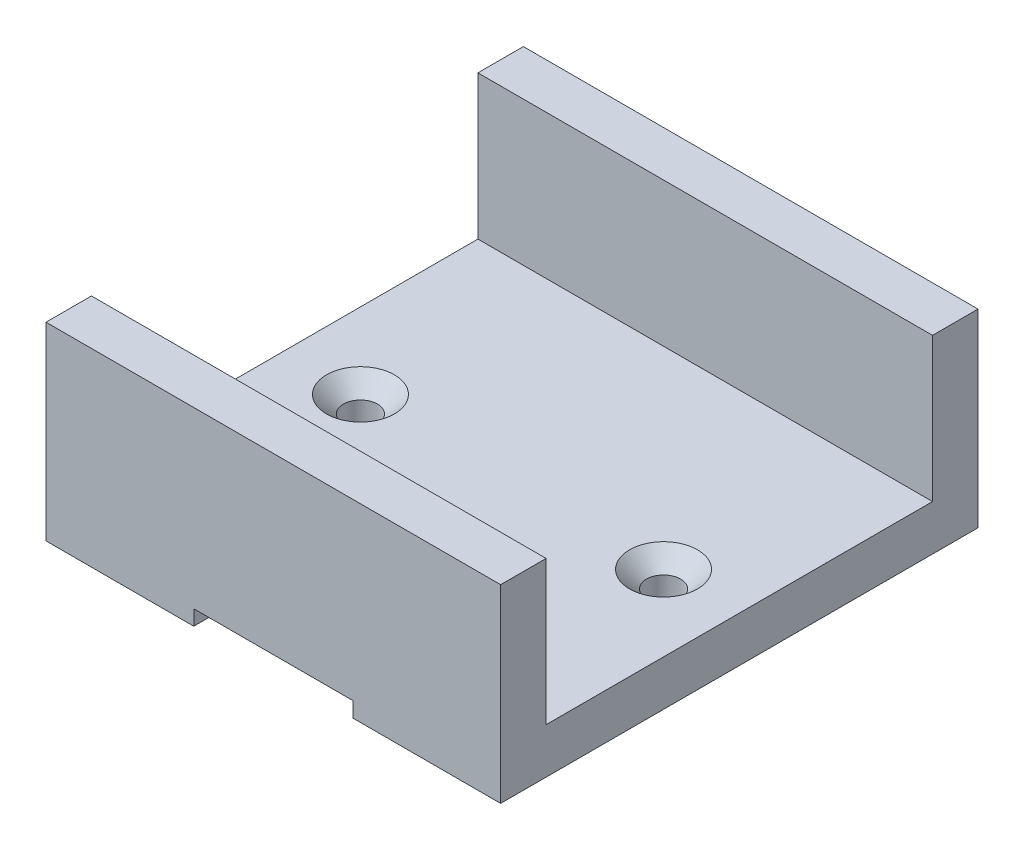
SolidWorks part; units mm, degrees
ref_plane "Front Plane" through (0, 0, 0) normal (0, 0, 1) x (1, 0, 0)
ref_plane "Top Plane" through (0, 0, 0) normal (0, 1, 0) x (1, 0, 0)
ref_plane "Right Plane" through (0, 0, 0) normal (1, 0, 0) x (0, 0, -1)
sketch "Sketch1" plane through (0, 0, 0) normal (1, 0, 0) x (0, 0, -1)
  line L1 (-31.5, -12.5) -> (31.5, -12.5)
  line L2 (-31.5, -12.5) -> (-31.5, 12.5)
  line L3 (-31.5, 12.5) -> (31.5, 12.5)
  line L4 (31.5, -12.5) -> (31.5, 12.5)
  line L5 (-31.5, -12.5) -> (31.5, 12.5) construction
  line L6 (-31.5, 12.5) -> (31.5, -12.5) construction
  line L7 (-25.5, -6.5) -> (25.5, -6.5)
  line L8 (-25.5, -6.5) -> (-25.5, 12.5)
  line L9 (-25.5, 12.5) -> (25.5, 12.5)
  line L10 (25.5, -6.5) -> (25.5, 12.5)
  line L11 (-25.5, -6.5) -> (25.5, 12.5) construction
  line L12 (-25.5, 12.5) -> (25.5, -6.5) construction
  point P0 (0, 0)
  point P6 (0, 3)
  point P11 (0, 0)
  dimension "D1" = 25
  dimension "D2" = 63
  dimension "D3" = 6
  dimension "D4" = 51
extrude "Boss-Extrude1" add sketch "Sketch1" along normal blind 60 contours L10 L7 L8 L3 L2 L1 L4
sketch "Sketch2" plane through (0, 0, 31.5) normal (0, 0, 1) x (1, 0, 0)
  line L0 (60, -12.5) -> (0, -12.5) construction
  line L1 (19.5, -10.5) -> (40.5, -10.5)
  line L2 (19.5, -10.5) -> (19.5, -12.5)
  line L3 (19.5, -12.5) -> (40.5, -12.5)
  line L4 (40.5, -10.5) -> (40.5, -12.5)
  line L5 (19.5, -10.5) -> (40.5, -12.5) construction
  line L6 (19.5, -12.5) -> (40.5, -10.5) construction
  point P0 (30, -11.5)
  point P5 (0, 0)
  dimension "D1" = 21
  dimension "D2" = 2
  dimension "D3" = 30
extrude "Cut-Extrude1" cut sketch "Sketch2" against normal through all
hole_wizard "CSK for M4 SFHCS1" positions "Sketch3" profile "Sketch4" countersink size "M4" standard "ANSI Metric" end condition through all
sketch "Sketch3" plane through (0, -6.5, 0) normal (0, 1, 0) x (1, 0, 0)
  line L0 (10, 0) -> (50, 0)
  point P1 (10, 0)
  point P2 (50, 0)
  dimension "D1" = 40
  dimension "D2" = 10
sketch "Sketch4" plane through (10, -6.5, 0) normal (1, 0, 0) x (0, 0, 1)
  line L0 (0, 0) -> (0, 6)
  line L1 (0, 6) -> (2.25, 6)
  line L2 (2.25, 6) -> (2.25, 2.23)
  line L3 (2.25, 2.23) -> (4.48, 0)
  line L5 (4.48, 0) -> (0, 0)
  line L6 (-2.25, 2.23) -> (-4.48, 0) construction
  line L11 (0, -6.35) -> (0, 107.95) construction
  dimension "Thru Hole Dia." = 4.5
  dimension "Thru Hole Depth" = 6
  dimension "Near C'Sink Dia." = 8.96
  dimension "Near C'Sink Angle" = 90
